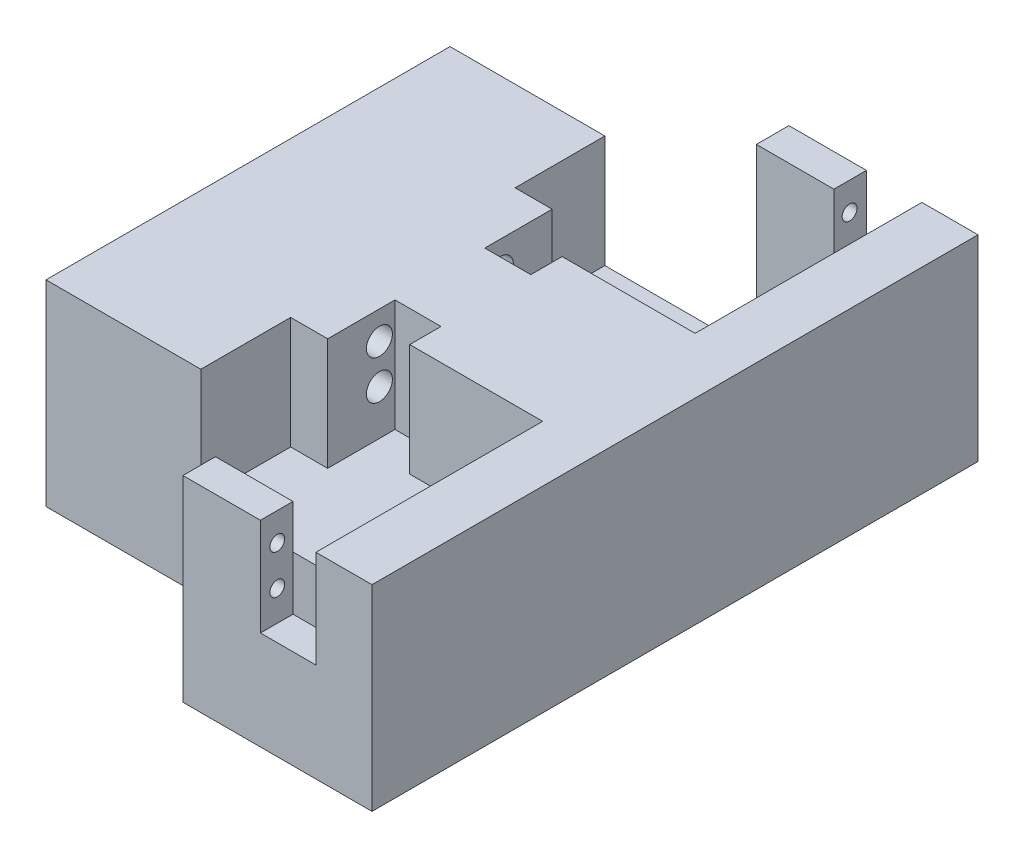
SolidWorks part; units mm, degrees
ref_plane "Front Plane" through (0, 0, 0) normal (0, 0, 1) x (1, 0, 0)
ref_plane "Top Plane" through (0, 0, 0) normal (0, 1, 0) x (1, 0, 0)
ref_plane "Right Plane" through (0, 0, 0) normal (1, 0, 0) x (0, 0, -1)
sketch "Sketch1" plane through (0, 0, 0) normal (0, 1, 0) x (1, 0, 0)
  line L1 (-44.45, -45.72) -> (44.45, -45.72)
  line L2 (-44.45, -45.72) -> (-44.45, 45.72)
  line L3 (-44.45, 45.72) -> (44.45, 45.72)
  line L4 (44.45, -45.72) -> (44.45, 45.72)
  line L5 (-44.45, -45.72) -> (44.45, 45.72) construction
  line L6 (-44.45, 45.72) -> (44.45, -45.72) construction
  point P0 (0, 0)
  dimension "D1" = 88.9
  dimension "D2" = 91.44
extrude "Boss-Extrude1" add sketch "Sketch1" along normal blind 44.45
sketch "Sketch2" plane through (0, 44.45, 0) normal (0, 1, 0) x (1, 0, 0)
  line L0 (44.45, 45.72) -> (-44.45, 45.72) construction
  line L1 (44.45, -45.72) -> (44.45, 45.72) construction
  line L2 (-44.45, -45.72) -> (44.45, -45.72) construction
  line L3 (-44.45, 45.72) -> (-44.45, -45.72) construction
  line L4 (44.45, 45.72) -> (-44.45, 45.72)
  line L5 (44.45, -45.72) -> (44.45, 45.72)
  line L6 (-44.45, -45.72) -> (44.45, -45.72)
  line L7 (-44.45, 45.72) -> (-44.45, -45.72)
  line L9 (-9.398, -45.72) -> (-1.016, -45.72)
  line L10 (-9.398, -45.72) -> (-9.398, -25.4)
  line L11 (-9.398, -25.4) -> (-1.016, -25.4)
  line L12 (-1.016, -45.72) -> (-1.016, -25.4)
  line L13 (-9.398, 45.72) -> (-1.016, 45.72)
  line L14 (-9.398, 45.72) -> (-9.398, 25.4)
  line L15 (-9.398, 25.4) -> (-1.016, 25.4)
  line L16 (-1.016, 45.72) -> (-1.016, 25.4)
  line L17 (-1.016, -45.72) -> (39.497, -45.72)
  line L18 (-1.016, -45.72) -> (-1.016, -10.16)
  line L19 (-1.016, -10.16) -> (39.497, -10.16)
  line L20 (39.497, -45.72) -> (39.497, -10.16)
  line L21 (-1.016, 45.72) -> (39.497, 45.72)
  line L22 (-1.016, 45.72) -> (-1.016, 10.16)
  line L23 (-1.016, 10.16) -> (39.497, 10.16)
  line L24 (39.497, 45.72) -> (39.497, 10.16)
  line L25 (39.497, -10.16) -> (9.398, -10.16)
  line L26 (39.497, -10.16) -> (39.497, -17.2466)
  line L27 (39.497, -17.2466) -> (9.398, -17.2466)
  line L28 (9.398, -10.16) -> (9.398, -17.2466)
  line L29 (39.497, 10.16) -> (9.398, 10.16)
  line L30 (39.497, 10.16) -> (39.497, 17.2466)
  line L31 (39.497, 17.2466) -> (9.398, 17.2466)
  line L32 (9.398, 10.16) -> (9.398, 17.2466)
  point P24 (9.398, -13.7033)
  line M32 (-44.45, -45.72) -> (44.45, -45.72)
  dimension "D1" = 53.848
  dimension "D2" = 8.382
  dimension "D3" = 4.953
  dimension "D4" = 35.56
  dimension "D5" = 20.32
  dimension "D6" = 7.0866
  dimension "D7" = 10.414
extrude "Cut-Extrude1" cut sketch "Sketch2" against normal blind 25.4 contours L6 L12 L11 L10 | L28 L19 L18 L12 L20 L27 M32 | L23 L32 L31 L24 L4 L16 L22 | L16 L4 L14 L15
sketch "Sketch3" plane through (0, 44.45, 0) normal (0, 1, 0) x (1, 0, 0)
  line L0 (44.45, -45.72) -> (44.45, 45.72) construction
  line L1 (39.497, -45.72) -> (44.45, -45.72) construction
  line L2 (44.45, 45.72) -> (39.497, 45.72) construction
  line L3 (44.45, -45.72) -> (44.45, 45.72)
  line L4 (39.497, -45.72) -> (44.45, -45.72)
  line L5 (44.45, 45.72) -> (39.497, 45.72)
  line L6 (52.197, 45.72) -> (52.197, -45.72)
  line L7 (39.497, 45.72) -> (52.197, 45.72)
  line L8 (39.497, 45.72) -> (39.497, 61.214)
  line L9 (39.497, 68.58) -> (52.197, 68.58)
  line L10 (52.197, 45.72) -> (52.197, 68.58)
  line L11 (39.497, -45.72) -> (52.197, -45.72)
  line L12 (39.497, -45.72) -> (39.497, -61.214)
  line L13 (39.497, -68.58) -> (52.197, -68.58)
  line L14 (52.197, -45.72) -> (52.197, -68.58)
  line L15 (9.398, -10.16) -> (9.398, -17.2466) construction
  line L16 (9.398, 10.16) -> (9.398, 17.2466) construction
  line L17 (9.398, -10.16) -> (9.398, -17.2466)
  line L18 (9.398, 10.16) -> (9.398, 17.2466)
  line L19 (9.398, -61.214) -> (39.497, -61.214)
  line L21 (39.497, -45.72) -> (39.497, -61.214)
  line L22 (39.497, -68.58) -> (9.398, -68.58)
  line L23 (9.398, -61.214) -> (9.398, -68.58)
  line L25 (39.497, 45.72) -> (39.497, 61.214)
  line L26 (39.497, 68.58) -> (9.398, 68.58)
  line L27 (9.398, 61.214) -> (9.398, 68.58)
  line L28 (9.398, 61.214) -> (39.497, 61.214)
  line M16 (39.497, -45.72) -> (44.45, -45.72)
  line M17 (44.45, -45.72) -> (44.45, 45.72)
  line M18 (44.45, 45.72) -> (39.497, 45.72)
  dimension "D1" = 22.86
  dimension "D2" = 12.7
  dimension "D3" = 7.366
extrude "Boss-Extrude2" add sketch "Sketch3" against normal up to surface (44.45 mm away) contours L7 L10 L9 L8 M18 | L11 L6 L7 M17 | L14 L11 L12 L13 M16 up to face at (0, 0, 0)
sketch "Sketch4" plane through (9.398, 0, 0) normal (-1, 0, 0) x (0, 0, 1)
  line L0 (61.214, 0) -> (68.58, 0) construction
  line L1 (68.58, 0) -> (68.58, 44.45) construction
  line L3 (61.214, 0) -> (61.214, 44.45) construction
  line L4 (10.16, 19.05) -> (17.2466, 19.05) construction
  line L5 (17.2466, 19.05) -> (17.2466, 44.45) construction
  line L7 (10.16, 19.05) -> (10.16, 44.45) construction
  line L8 (-10.16, 19.05) -> (-17.2466, 19.05) construction
  line L9 (-10.16, 19.05) -> (-10.16, 44.45) construction
  line L11 (-17.2466, 19.05) -> (-17.2466, 44.45) construction
  line L12 (-61.214, 0) -> (-68.58, 0) construction
  line L14 (-61.214, 0) -> (-61.214, 44.45) construction
  line L15 (-68.58, 0) -> (-68.58, 44.45) construction
  line L16 (61.214, 0) -> (68.58, 0)
  line L17 (68.58, 0) -> (68.58, 44.45)
  line L18 (61.214, 44.45) -> (68.58, 44.45)
  line L19 (61.214, 0) -> (61.214, 44.45)
  line L20 (10.16, 19.05) -> (17.2466, 19.05)
  line L21 (17.2466, 19.05) -> (17.2466, 44.45)
  line L22 (10.16, 44.45) -> (17.2466, 44.45)
  line L23 (10.16, 19.05) -> (10.16, 44.45)
  line L24 (-10.16, 19.05) -> (-17.2466, 19.05)
  line L25 (-10.16, 19.05) -> (-10.16, 44.45)
  line L26 (-10.16, 44.45) -> (-17.2466, 44.45)
  line L27 (-17.2466, 19.05) -> (-17.2466, 44.45)
  line L28 (-61.214, 0) -> (-68.58, 0)
  line L29 (-61.214, 44.45) -> (-68.58, 44.45)
  line L30 (-61.214, 0) -> (-61.214, 44.45)
  line L31 (-68.58, 0) -> (-68.58, 44.45)
  circle A0 centre (-64.77, 29.21) radius 1.6764
  circle A1 centre (-64.77, 38.1) radius 1.6764
  circle A2 centre (-13.6906, 38.1) radius 1.6764
  circle A3 centre (-13.6906, 29.21) radius 1.6764
  circle A4 centre (13.6906, 38.1) radius 1.6764
  circle A5 centre (13.6906, 29.21) radius 1.6764
  circle A6 centre (64.77, 38.1) radius 1.6764
  circle A7 centre (64.77, 29.21) radius 1.6764
  dimension "D2" = 6.35
  dimension "D7" = 3.3528
  dimension "D1" = 8.89
  dimension "D3" = 3.556
  dimension "D4" = 3.556
  dimension "D5" = 3.556
  dimension "D6" = 3.556
  dimension "D8" = 6.35
extrude "Cut-Extrude4" cut sketch "Sketch4" against normal blind 22.098 contours A0 | A1 | A3 | A2 | A5 | A4 | A7 | A6
sketch "Sketch5" plane through (-44.45, 0, 0) normal (-1, 0, 0) x (0, 0, 1)
  circle A2 centre (-13.6906, 38.1) radius 2.9464
  circle A3 centre (-13.6906, 38.1) radius 2.9464
  circle A5 centre (-13.6906, 29.21) radius 2.9464
  circle A16 centre (-13.6906, 29.21) radius 2.9464
  circle A18 centre (13.6906, 38.1) radius 2.9464
  circle A19 centre (13.6906, 38.1) radius 2.9464
  circle A21 centre (13.6906, 29.21) radius 2.9464
  circle A22 centre (13.6906, 29.21) radius 2.9464
  dimension "D1" = 1.27
  dimension "D2" = 1.27
  dimension "D3" = 1.27
  dimension "D4" = 1.27
extrude "Cut-Extrude6" cut sketch "Sketch5" against normal up to surface (43.434 mm away) up to face at (-1.016, 31.75, -17.78)
sketch "Sketch7" plane through (0, 44.45, 0) normal (0, 1, 0) x (1, 0, 0)
  line L0 (39.497, 61.214) -> (39.497, 17.2466) construction
  line L1 (39.497, -61.214) -> (39.497, -17.2466) construction
  line L2 (9.398, -61.214) -> (39.497, -61.214) construction
  line L3 (9.398, 61.214) -> (39.497, 61.214) construction
  line L4 (39.497, 61.214) -> (39.497, 17.2466)
  line L5 (39.497, -61.214) -> (39.497, -17.2466)
  line L6 (9.398, -61.214) -> (39.497, -61.214)
  line L7 (9.398, 61.214) -> (39.497, 61.214)
  line L8 (9.398, 68.58) -> (52.197, 68.58) construction
  line L9 (39.497, 61.214) -> (26.9447, 61.214)
  line L10 (39.497, 61.214) -> (39.497, 68.58)
  line L11 (39.497, 68.58) -> (26.9447, 68.58)
  line L12 (26.9447, 61.214) -> (26.9447, 68.58)
  line L13 (52.197, -68.58) -> (9.398, -68.58) construction
  line L14 (39.497, -61.214) -> (26.9447, -61.214)
  line L15 (39.497, -61.214) -> (39.497, -68.58)
  line L16 (39.497, -68.58) -> (26.9447, -68.58)
  line L17 (26.9447, -61.214) -> (26.9447, -68.58)
  line M12 (39.497, -61.214) -> (9.398, -61.214)
  line M14 (9.398, -68.58) -> (52.197, -68.58)
extrude "Cut-Extrude7" cut sketch "Sketch7" against normal blind 22.098 contours L17 L15 M12 M14 | L10 L11 L12 L9
